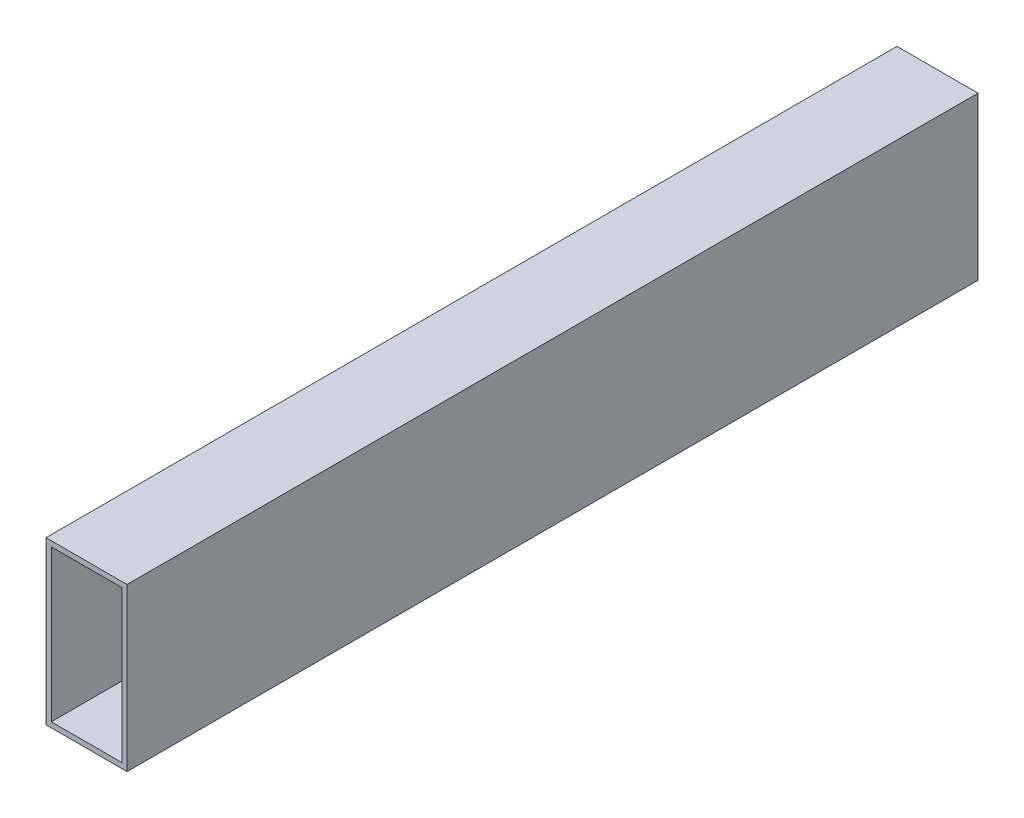
SolidWorks part; units mm, degrees
ref_plane "Front Plane" through (0, 0, 0) normal (0, 0, 1) x (1, 0, 0)
ref_plane "Top Plane" through (0, 0, 0) normal (0, 1, 0) x (1, 0, 0)
ref_plane "Right Plane" through (0, 0, 0) normal (1, 0, 0) x (0, 0, -1)
sketch "Sketch1" plane through (0, 0, 0) normal (0, 0, 1) x (1, 0, 0)
  line L1 (-48.4372, -30.1994) -> (-23.0372, -30.1994)
  line L2 (-48.4372, -30.1994) -> (-48.4372, 20.6006)
  line L3 (-48.4372, 20.6006) -> (-23.0372, 20.6006)
  line L4 (-23.0372, -30.1994) -> (-23.0372, 20.6006)
  dimension "D1" = 25.4
  dimension "D2" = 50.8
extrude "Boss-Extrude1" add sketch "Sketch1" along normal blind 266.7
sketch "Sketch2" plane through (0, 0, 266.7) normal (0, 0, 1) x (1, 0, 0)
  line L0 (-48.4372, 20.6006) -> (-48.4372, -30.1994) construction
  line L1 (-46.7862, 18.9496) -> (-24.6882, 18.9496)
  line L2 (-46.7862, 18.9496) -> (-46.7862, -28.5484)
  line L3 (-46.7862, -28.5484) -> (-24.6882, -28.5484)
  line L4 (-24.6882, 18.9496) -> (-24.6882, -28.5484)
  line L5 (-46.7862, 18.9496) -> (-24.6882, -28.5484) construction
  line L6 (-46.7862, -28.5484) -> (-24.6882, 18.9496) construction
  line L7 (-23.0372, -30.1994) -> (-23.0372, 20.6006) construction
  line L8 (-23.0372, 20.6006) -> (-48.4372, 20.6006) construction
  line L9 (-48.4372, -30.1994) -> (-23.0372, -30.1994) construction
  point P0 (-35.7372, -4.7994)
  dimension "D1" = 1.651
  dimension "D2" = 1.651
  dimension "D3" = 1.651
  dimension "D4" = 1.651
extrude "Cut-Extrude1" cut sketch "Sketch2" against normal through all
